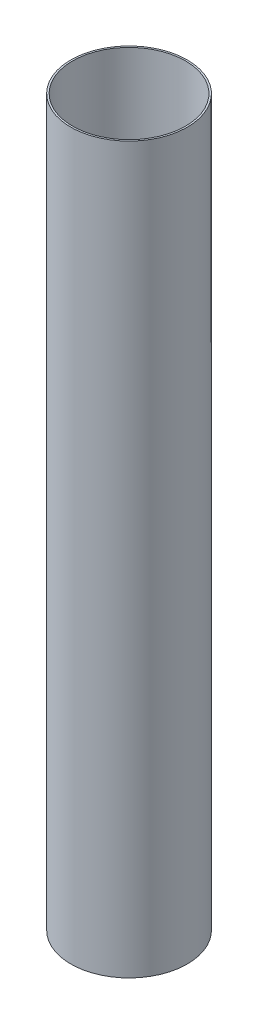
SolidWorks part; units mm, degrees
ref_plane "Front Plane" through (0, 0, 0) normal (1, 0, 0) x (0, 1, 0)
ref_plane "Top Plane" through (0, 0, 0) normal (0, 0, 1) x (0, 1, 0)
ref_plane "Right Plane" through (0, 0, 0) normal (0, 1, 0) x (-1, 0, 0)
ref_plane "Plane1" through (0, 150, 0) normal (0, 1, 0) x (1, 0, 0)
sketch "Sketch1" plane through (0, 150, 0) normal (0, 1, 0) x (1, 0, 0)
  circle A0 centre (0, 0) radius 51.054
  circle A1 centre (0, 0) radius 49.53
  dimension "D1" = 102.108
  dimension "3.9\"" = 99.06
extrude "Boss-Extrude1" add sketch "Sketch1" along normal blind 635 contours A0 | A1
